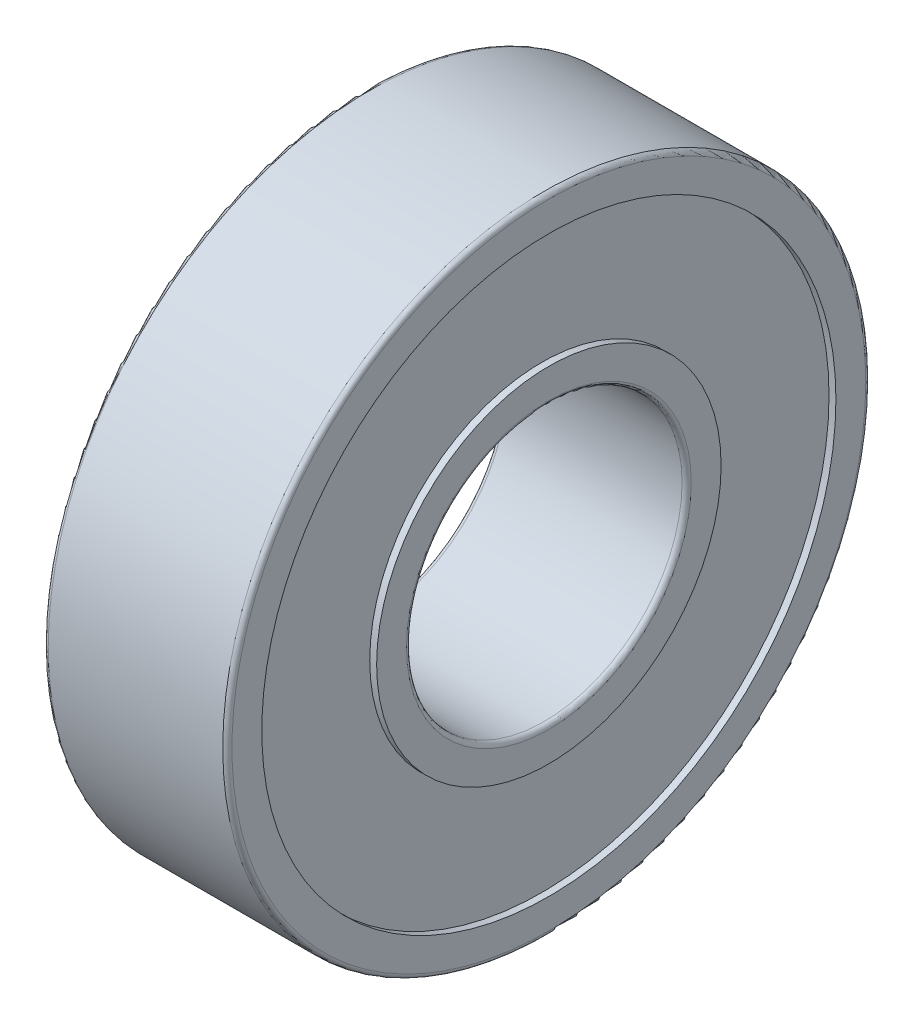
SolidWorks part; units mm, degrees
material "Plain Carbon Steel"
ref_plane "Front Plane" through (0, 0, 0) normal (0, 0, 1) x (1, 0, 0)
ref_plane "Top Plane" through (0, 0, 0) normal (0, 1, 0) x (1, 0, 0)
ref_plane "Right Plane" through (0, 0, 0) normal (1, 0, 0) x (0, 0, -1)
sketch "Sketch1" plane through (0, 0, 0) normal (0, 0, 1) x (1, 0, 0)
  line L0 (4, 6) -> (-4, 6)
  line L1 (-4, 6) -> (-4, 7.5)
  line L2 (-4, 7.5) -> (-3.7, 7.5)
  line L3 (-3.7, 7.5) -> (-3.7, 12.5)
  line L4 (-3.7, 12.5) -> (-4, 12.5)
  line L5 (-4, 12.5) -> (-4, 14)
  line L6 (-4, 14) -> (4, 14)
  line L7 (0, 14) -> (0, 6) construction
  line L8 (4, 12.5) -> (4, 14)
  line L9 (3.7, 12.5) -> (4, 12.5)
  line L10 (3.7, 7.5) -> (3.7, 12.5)
  line L11 (4, 7.5) -> (3.7, 7.5)
  line L12 (4, 6) -> (4, 7.5)
  line L13 (0, 0) -> (-4.3663, 0) construction
  dimension "D1" = 12
  dimension "D2" = 28
  dimension "D3" = 8
  dimension "D4" = 1.5
  dimension "D5" = 1.5
  dimension "D6" = 0.3
revolve "Revolve1" add sketch "Sketch1" angle 360 about L13
fillet "Fillet1" radius 0.2 4 edges at (-4, 0, -14) (4, 0, -14) (-4, 0, -6) (4, 0, -6)
